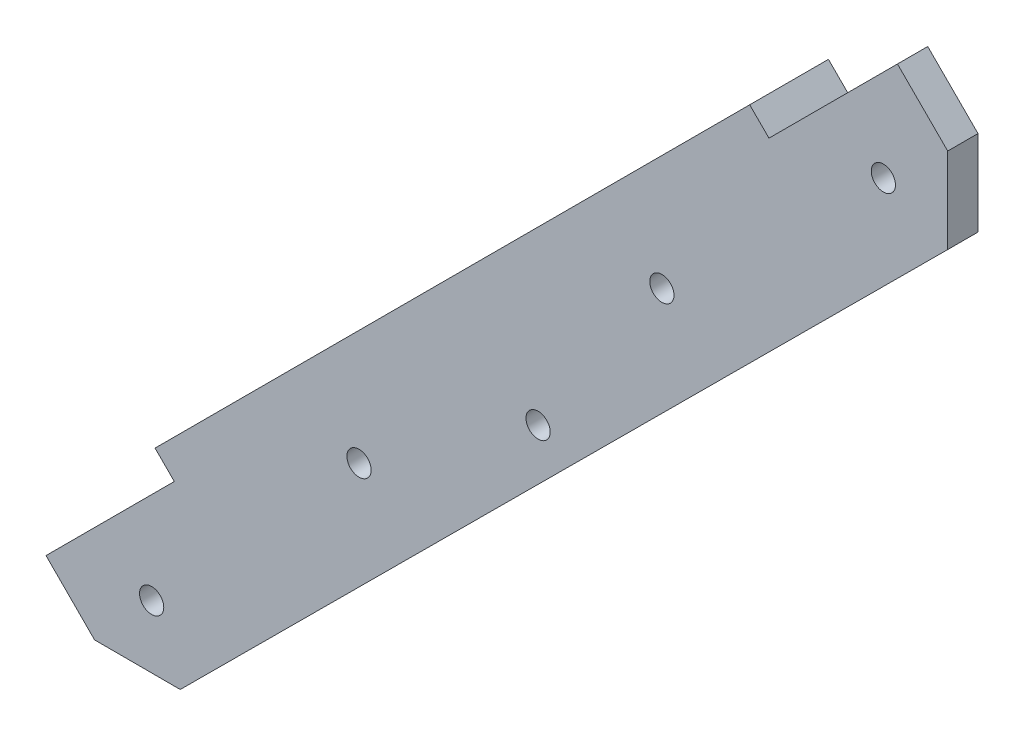
SolidWorks part; units mm, degrees
ref_plane "Front Plane" through (0, 0, 0) normal (0, 0, 1) x (1, 0, 0)
ref_plane "Top Plane" through (0, 0, 0) normal (0, 1, 0) x (1, 0, 0)
ref_plane "Right Plane" through (0, 0, 0) normal (1, 0, 0) x (0, 0, -1)
sketch "Sketch1" plane through (0, 0, 0) normal (0, 0, 1) x (1, 0, 0)
  line L0 (46.6464, 27) -> (145, 125)
  line L1 (46.6464, 27) -> (25.3951, 5.825)
  line L2 (25.3951, 5.825) -> (10.3192, 20.9553)
  line L3 (4.5, 15.136) -> (31.5052, 42.1412) construction
  line L4 (145, 125) -> (166.2514, 146.175)
  line L5 (166.2514, 146.175) -> (150.8952, 161.5312)
  line L6 (129.682, 140.318) -> (156.864, 167.5) construction
  line L7 (150.8952, 161.5312) -> (129.682, 140.318)
  line L8 (129.682, 140.318) -> (126.5, 143.5)
  line L9 (126.5, 143.5) -> (28.3232, 45.3232)
  line L10 (28.3232, 45.3232) -> (31.5052, 42.1412)
  line L11 (31.5052, 42.1412) -> (10.3192, 20.9553)
  dimension "D1" = 30
  dimension "D2" = 30
extrude "Boss-Extrude1" add sketch "Sketch1" along normal blind 5
sketch "Sketch2" plane through (0, 0, 5) normal (0, 0, 1) x (1, 0, 0)
  circle A0 centre (27.7621, 23.2569) radius 2
  circle A1 centre (148.5663, 144.0611) radius 2
  dimension "D1" = 4
  dimension "D2" = 4
extrude "Cut-Extrude1" cut sketch "Sketch2" against normal blind 15
sketch "Sketch3" plane through (0, 0, 0) normal (0, 0, -1) x (-1, 0, 0)
  line L0 (-28.3232, 45.3232) -> (-46.6134, 26.9671)
  line L1 (-25.3951, 5.825) -> (-166.2514, 146.175) construction
  line L2 (-46.6134, 26.9671) -> (-145, 125)
  line L3 (-126.5, 143.5) -> (-145, 125) construction
  line L4 (-145, 125) -> (-126.5, 143.5)
  line L5 (-126.5, 143.5) -> (-28.3232, 45.3232)
extrude "Boss-Extrude2" add sketch "Sketch3" along normal up to surface (8 mm away)
chamfer "Chamfer1" distance 10 angle 45 2 edges at (166.2514, 146.175, 2.5) (25.3951, 5.825, 2.5)
sketch "Sketch4" plane through (0, 0, 5) normal (0, 0, 1) x (1, 0, 0)
  circle A0 centre (62, 60) radius 2
  circle A1 centre (112, 110) radius 2
  dimension "D1" = 4
  dimension "D2" = 4
extrude "Cut-Extrude2" cut sketch "Sketch4" against normal up to next
sketch "Sketch5" plane through (0, 0, -8) normal (0, 0, -1) x (-1, 0, 0)
  circle A0 centre (-62, 60) radius 4
  circle A1 centre (-112, 110) radius 4
  dimension "D1" = 8
  dimension "D2" = 8
extrude "Cut-Extrude3" cut sketch "Sketch5" against normal blind 3
sketch "Sketch6" plane through (0, 0, -8) normal (0, 0, -1) x (-1, 0, 0)
  line L0 (-46.6134, 26.9671) -> (-145, 125) construction
  line L1 (-92.2204, 89.3678) -> (-105.6047, 85.7815)
  line L2 (-105.6047, 85.7815) -> (-109.191, 72.3972)
  line L3 (-109.191, 72.3972) -> (-99.393, 62.5993)
  line L4 (-99.393, 62.5993) -> (-86.0087, 66.1856)
  line L5 (-86.0087, 66.1856) -> (-82.4224, 79.5698)
  line L6 (-82.4224, 79.5698) -> (-92.2204, 89.3678)
  line L7 (-126.5, 143.5) -> (-28.3232, 45.3232) construction
  circle A0 centre (-95.8067, 75.9835) radius 12 construction
  dimension "D1" = 24
extrude "Cut-Extrude4" cut sketch "Sketch6" against normal blind 7
sketch "Sketch7" plane through (0, 0, -1) normal (0, 0, -1) x (-1, 0, 0)
  line L0 (-87.3214, 84.4688) -> (-91.5641, 80.2262) construction
  line L1 (-82.4224, 79.5698) -> (-92.2204, 89.3678) construction
  circle A0 centre (-91.5641, 80.2262) radius 2
  dimension "D1" = 4
  dimension "D2" = 6
extrude "Cut-Extrude5" cut sketch "Sketch7" against normal blind 17
